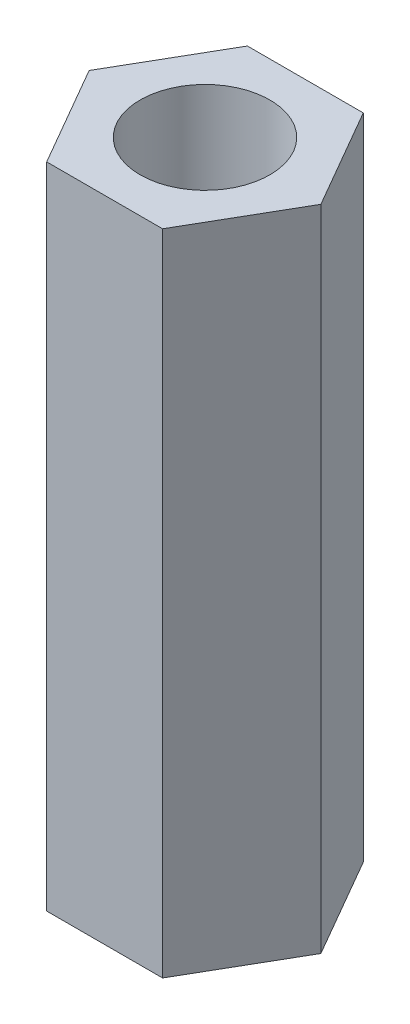
SolidWorks part; units mm, degrees
ref_plane "Front Plane" through (0, 0, 0) normal (0, 0, 1) x (1, 0, 0)
ref_plane "Top Plane" through (0, 0, 0) normal (0, 1, 0) x (1, 0, 0)
ref_plane "Right Plane" through (0, 0, 0) normal (1, 0, 0) x (0, 0, -1)
sketch "Sketch1" plane through (0, 0, 0) normal (0, 1, 0) x (1, 0, 0)
  line L1 (2.6789, 0) -> (1.3395, 2.32)
  line L2 (1.3395, 2.32) -> (-1.3395, 2.32)
  line L3 (-1.3395, 2.32) -> (-2.6789, 0)
  line L4 (-2.6789, 0) -> (-1.3395, -2.32)
  line L5 (-1.3395, -2.32) -> (1.3395, -2.32)
  line L6 (1.3395, -2.32) -> (2.6789, 0)
  circle A0 centre (0, 0) radius 2.32 construction
  circle A1 centre (0, 0) radius 1.5
  point P10 (0, 0)
  dimension "D2" = 3
  dimension "D1" = 4.64
extrude "Boss-Extrude1" add sketch "Sketch1" along normal mid plane 15
